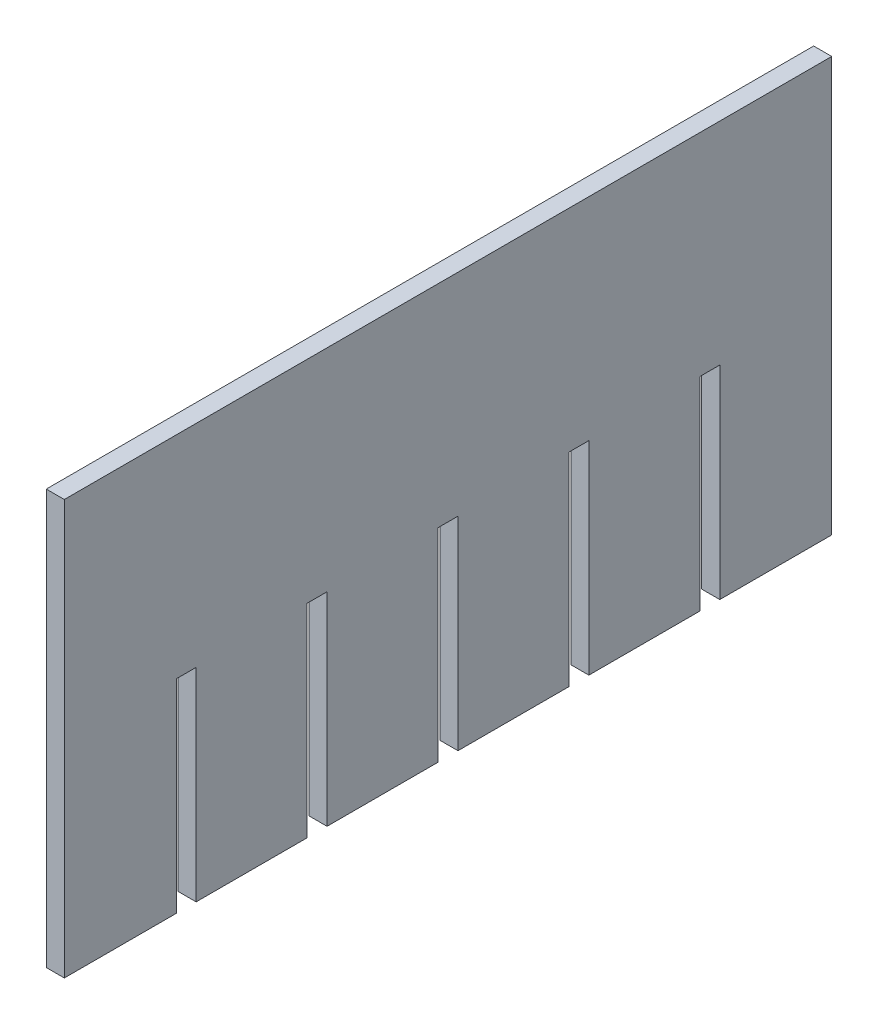
SolidWorks part; units mm, degrees
ref_plane "Спереди" through (0, 0, 0) normal (0, 0, 1) x (1, 0, 0)
ref_plane "Сверху" through (0, 0, 0) normal (0, 1, 0) x (1, 0, 0)
ref_plane "Справа" through (0, 0, 0) normal (1, 0, 0) x (0, 0, -1)
sketch "Эскиз1" plane through (0, 0, 0) normal (1, 0, 0) x (0, 0, -1)
  line L0 (0, 0) -> (0, 91.8)
  line L1 (0, 91.8) -> (170, 91.8)
  line L2 (170, 91.8) -> (170, 0)
  line L3 (0, 0) -> (170, 0) construction
  line L4 (0, 0) -> (24.8, 0)
  line L5 (24.8, 0) -> (24.8, 45)
  line L6 (24.8, 45) -> (29.2, 45)
  line L7 (29.2, 45) -> (29.2, 0)
  line L8 (27, 45) -> (27, 13.2444) construction
  line L9 (29.2, 0) -> (53.8, 0)
  line L10 (53.8, 0) -> (53.8, 45)
  line L11 (53.8, 45) -> (58.2, 45)
  line L12 (58.2, 45) -> (58.2, 0)
  line L13 (58.2, 0) -> (82.8, 0)
  line L14 (82.8, 0) -> (82.8, 45)
  line L15 (82.8, 45) -> (87.2, 45)
  line L16 (87.2, 45) -> (87.2, 0)
  line L17 (87.2, 0) -> (111.8, 0)
  line L18 (111.8, 0) -> (111.8, 45)
  line L19 (111.8, 45) -> (116.2, 45)
  line L20 (116.2, 45) -> (116.2, 0)
  line L21 (116.2, 0) -> (140.8, 0)
  line L22 (140.8, 0) -> (140.8, 45)
  line L23 (140.8, 45) -> (145.2, 45)
  line L24 (145.2, 45) -> (145.2, 0)
  line L25 (143, 45) -> (143, 55.136) construction
  line L30 (29.2, 45) -> (53.8, 45) construction
  line L31 (170, 0) -> (145.2, 0)
  dimension "D1" = 29
  dimension "D2" = 4.4
  dimension "D3" = 45
  dimension "D4" = 91.8
  dimension "D6" = 27
  dimension "D7" = 27
  dimension "D8" = 24.8
  dimension "D9" = 24.8
  dimension "D5" = 5
extrude "Бобышка-Вытянуть1" add sketch "Эскиз1" along normal blind 4
